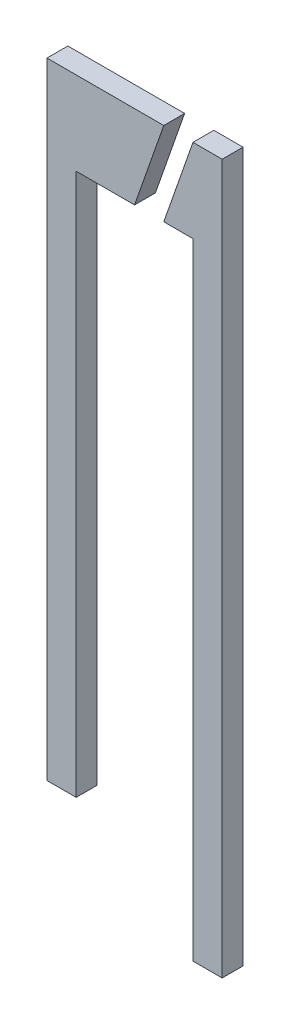
SolidWorks part; units mm, degrees
ref_plane "Front Plane" through (0, 0, 0) normal (0, 0, 1) x (1, 0, 0)
ref_plane "Top Plane" through (0, 0, 0) normal (0, 1, 0) x (1, 0, 0)
ref_plane "Right Plane" through (0, 0, 0) normal (1, 0, 0) x (0, 0, -1)
sketch "Sketch1" plane through (0, 0, 0) normal (0, 0, 1) x (1, 0, 0)
  line L0 (1.4, -15.7293) -> (2.1, -15.7293)
  line L1 (2.1, -15.7293) -> (2.1, -32.7293)
  line L2 (1.4, -15.7293) -> (0.7, -17.7293)
  line L3 (0.7, -17.7293) -> (1.4, -17.7293)
  line L4 (1.4, -17.7293) -> (1.4, -32.7293)
  line L5 (1.4, -32.7293) -> (2.1, -32.7293)
  line L6 (0.7, -15.7293) -> (0, -17.7293)
  line L7 (0, -17.7293) -> (-1.4, -17.7293)
  line L8 (-1.4, -17.7293) -> (-1.4, -30.7293)
  line L9 (-1.4, -30.7293) -> (-2.1, -30.7293)
  line L10 (-2.1, -30.7293) -> (-2.1, -15.7293)
  line L11 (-2.1, -15.7293) -> (0.7, -15.7293)
  line L12 (0, 46.9906) -> (0, -46.9906) construction
  dimension "D1" = 0.7
  dimension "D2" = 17
  dimension "D3" = 15
  dimension "D4" = 0.7
  dimension "D5" = 1.4
  dimension "D6" = 0.7
  dimension "D7" = 0.7
  dimension "D8" = 0.7
  dimension "D9" = 0.7
  dimension "D10" = 2
extrude "Boss-Extrude1" add sketch "Sketch1" along normal blind 0.5
